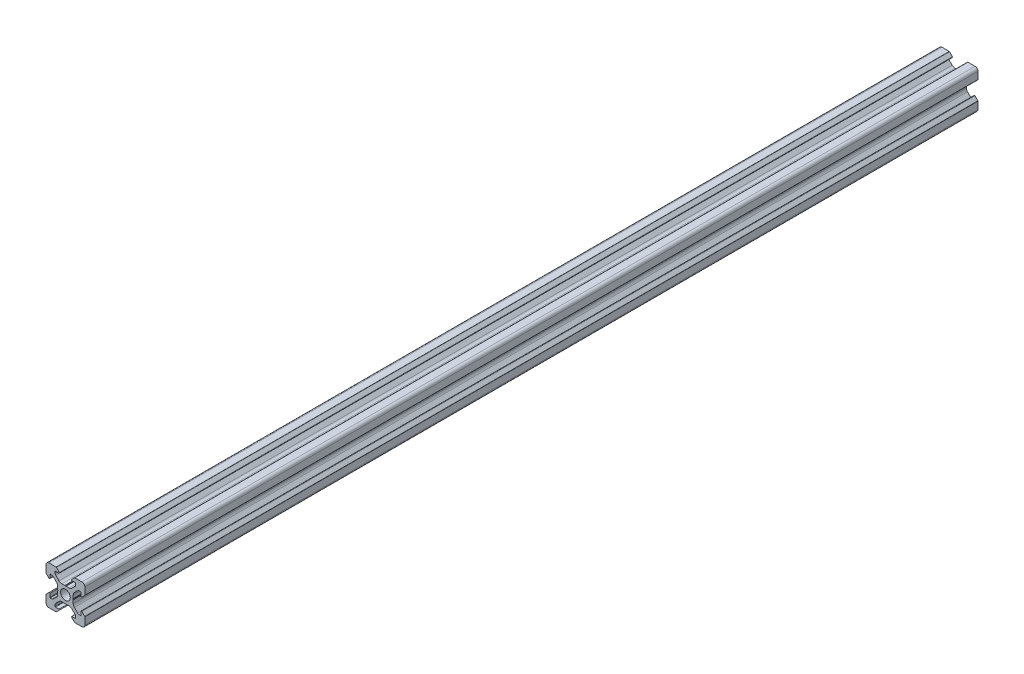
SolidWorks part; units mm, degrees
ref_plane "Спереди" through (0, 0, 0) normal (0, 0, 1) x (1, 0, 0)
ref_plane "Сверху" through (0, 0, 0) normal (0, 1, 0) x (1, 0, 0)
ref_plane "Справа" through (0, 0, 0) normal (1, 0, 0) x (0, 0, -1)
sketch "Model" plane through (0, 0, 0) normal (0, 0, 1) x (1, 0, 0)
  line L0 (18.9421, 33.3622) -> (18.9421, 34.9233)
  line L1 (18.3564, 36.3375) -> (16.6623, 38.0316)
  line L2 (15.9551, 38.3245) -> (15.1421, 38.3245)
  line L3 (14.9421, 38.1245) -> (14.9421, 36.3545)
  line L4 (13.0154, 37.6777) -> (14.5154, 36.1777)
  line L5 (12.9421, 37.8545) -> (12.9421, 41.5245)
  line L6 (18.2889, 42.9513) -> (19.7889, 41.4513)
  line L7 (22.7606, 36.9697) -> (22.9421, 36.8245)
  line L8 (23.1237, 36.9697) -> (22.9421, 36.8245)
  line L9 (23.2798, 37.0245) -> (24.8409, 37.0245)
  line L10 (26.2551, 37.6103) -> (27.9493, 39.3044)
  line L11 (28.2421, 40.0115) -> (28.2421, 40.8245)
  line L12 (28.0421, 41.0245) -> (26.2721, 41.0245)
  line L13 (27.5954, 42.9513) -> (26.0954, 41.4513)
  line L14 (27.7721, 43.0245) -> (31.4421, 43.0245)
  line L15 (32.9421, 37.8545) -> (32.9421, 41.5245)
  line L16 (32.8689, 37.6777) -> (31.3689, 36.1777)
  line L17 (30.9421, 38.1245) -> (30.9421, 36.3545)
  line L18 (29.9292, 38.3245) -> (30.7421, 38.3245)
  line L19 (27.5279, 36.3375) -> (29.222, 38.0316)
  line L20 (26.9421, 33.3622) -> (26.9421, 34.9233)
  line L21 (26.8874, 33.206) -> (26.7421, 33.0245)
  line L22 (26.8874, 32.843) -> (26.7421, 33.0245)
  line L23 (26.9421, 32.6868) -> (26.9421, 31.1257)
  line L24 (27.5279, 29.7115) -> (29.222, 28.0174)
  line L25 (29.9292, 27.7245) -> (30.7421, 27.7245)
  line L26 (30.9421, 27.9245) -> (30.9421, 29.6945)
  line L27 (32.8689, 28.3713) -> (31.3689, 29.8713)
  line L28 (32.9421, 28.1945) -> (32.9421, 24.5245)
  line L29 (27.7721, 23.0245) -> (31.4421, 23.0245)
  line L30 (27.5954, 23.0977) -> (26.0954, 24.5977)
  line L31 (28.0421, 25.0245) -> (26.2721, 25.0245)
  line L32 (28.2421, 26.0375) -> (28.2421, 25.2245)
  line L33 (26.2551, 28.4387) -> (27.9493, 26.7446)
  line L34 (23.2798, 29.0245) -> (24.8409, 29.0245)
  line L35 (23.1237, 29.0793) -> (22.9421, 29.2245)
  line L36 (22.7606, 29.0793) -> (22.9421, 29.2245)
  line L37 (19.6292, 28.4387) -> (17.935, 26.7446)
  line L38 (17.6421, 26.0375) -> (17.6421, 25.2245)
  line L39 (17.8421, 25.0245) -> (19.6121, 25.0245)
  line L40 (18.2889, 23.0977) -> (19.7889, 24.5977)
  line L41 (18.1121, 23.0245) -> (14.4421, 23.0245)
  line L42 (12.9421, 28.1945) -> (12.9421, 24.5245)
  line L43 (13.0154, 28.3713) -> (14.5154, 29.8713)
  line L44 (14.9421, 27.9245) -> (14.9421, 29.6945)
  line L45 (15.9551, 27.7245) -> (15.1421, 27.7245)
  line L46 (18.3564, 29.7115) -> (16.6623, 28.0174)
  line L47 (18.9421, 32.6868) -> (18.9421, 31.1257)
  line L48 (18.9969, 32.843) -> (19.1421, 33.0245)
  line L49 (18.9969, 33.206) -> (19.1421, 33.0245)
  line L50 (22.6045, 29.0245) -> (21.0434, 29.0245)
  line L51 (22.6045, 37.0245) -> (21.0434, 37.0245)
  line L52 (19.6292, 37.6103) -> (17.935, 39.3044)
  line L53 (17.6421, 40.0115) -> (17.6421, 40.8245)
  line L54 (17.8421, 41.0245) -> (19.6121, 41.0245)
  line L55 (18.1121, 43.0245) -> (14.4421, 43.0245)
  arc A0 (18.9421, 33.3622) -> (18.9969, 33.206) centre (19.1921, 33.3622) ccw
  arc A1 (18.9421, 34.9233) -> (18.3564, 36.3375) centre (16.9421, 34.9233) ccw
  arc A2 (16.6623, 38.0316) -> (15.9551, 38.3245) centre (15.9551, 37.3245) ccw
  arc A3 (15.1421, 38.3245) -> (14.9421, 38.1245) centre (15.1421, 38.1245) ccw
  arc A4 (14.5154, 36.1777) -> (14.9421, 36.3545) centre (14.6921, 36.3545) ccw
  arc A5 (12.9421, 37.8545) -> (13.0154, 37.6777) centre (13.1921, 37.8545) ccw
  arc A6 (14.4421, 43.0245) -> (12.9421, 41.5245) centre (14.4421, 41.5245) ccw
  arc A7 (18.2889, 42.9513) -> (18.1121, 43.0245) centre (18.1121, 42.7745) ccw
  arc A8 (19.6121, 41.0245) -> (19.7889, 41.4513) centre (19.6121, 41.2745) ccw
  arc A9 (17.8421, 41.0245) -> (17.6421, 40.8245) centre (17.8421, 40.8245) ccw
  arc A10 (17.6421, 40.0115) -> (17.935, 39.3044) centre (18.6421, 40.0115) ccw
  arc A11 (19.6292, 37.6103) -> (21.0434, 37.0245) centre (21.0434, 39.0245) ccw
  arc A12 (22.7606, 36.9697) -> (22.6045, 37.0245) centre (22.6045, 36.7745) ccw
  arc A13 (23.2798, 37.0245) -> (23.1237, 36.9697) centre (23.2798, 36.7745) ccw
  arc A14 (24.8409, 37.0245) -> (26.2551, 37.6103) centre (24.8409, 39.0245) ccw
  arc A15 (27.9493, 39.3044) -> (28.2421, 40.0115) centre (27.2421, 40.0115) ccw
  arc A16 (28.2421, 40.8245) -> (28.0421, 41.0245) centre (28.0421, 40.8245) ccw
  arc A17 (26.0954, 41.4513) -> (26.2721, 41.0245) centre (26.2721, 41.2745) ccw
  arc A18 (27.7721, 43.0245) -> (27.5954, 42.9513) centre (27.7721, 42.7745) ccw
  arc A19 (32.9421, 41.5245) -> (31.4421, 43.0245) centre (31.4421, 41.5245) ccw
  arc A20 (32.8689, 37.6777) -> (32.9421, 37.8545) centre (32.6921, 37.8545) ccw
  arc A21 (30.9421, 36.3545) -> (31.3689, 36.1777) centre (31.1921, 36.3545) ccw
  arc A22 (30.9421, 38.1245) -> (30.7421, 38.3245) centre (30.7421, 38.1245) ccw
  arc A23 (29.9292, 38.3245) -> (29.222, 38.0316) centre (29.9292, 37.3245) ccw
  arc A24 (27.5279, 36.3375) -> (26.9421, 34.9233) centre (28.9421, 34.9233) ccw
  arc A25 (26.8874, 33.206) -> (26.9421, 33.3622) centre (26.6921, 33.3622) ccw
  arc A26 (26.9421, 32.6868) -> (26.8874, 32.843) centre (26.6921, 32.6868) ccw
  arc A27 (26.9421, 31.1257) -> (27.5279, 29.7115) centre (28.9421, 31.1257) ccw
  arc A28 (29.222, 28.0174) -> (29.9292, 27.7245) centre (29.9292, 28.7245) ccw
  arc A29 (30.7421, 27.7245) -> (30.9421, 27.9245) centre (30.7421, 27.9245) ccw
  arc A30 (31.3689, 29.8713) -> (30.9421, 29.6945) centre (31.1921, 29.6945) ccw
  arc A31 (32.9421, 28.1945) -> (32.8689, 28.3713) centre (32.6921, 28.1945) ccw
  arc A32 (31.4421, 23.0245) -> (32.9421, 24.5245) centre (31.4421, 24.5245) ccw
  arc A33 (27.5954, 23.0977) -> (27.7721, 23.0245) centre (27.7721, 23.2745) ccw
  arc A34 (26.2721, 25.0245) -> (26.0954, 24.5977) centre (26.2721, 24.7745) ccw
  arc A35 (28.0421, 25.0245) -> (28.2421, 25.2245) centre (28.0421, 25.2245) ccw
  arc A36 (28.2421, 26.0375) -> (27.9493, 26.7446) centre (27.2421, 26.0375) ccw
  arc A37 (26.2551, 28.4387) -> (24.8409, 29.0245) centre (24.8409, 27.0245) ccw
  arc A38 (23.1237, 29.0793) -> (23.2798, 29.0245) centre (23.2798, 29.2745) ccw
  arc A39 (22.6045, 29.0245) -> (22.7606, 29.0793) centre (22.6045, 29.2745) ccw
  arc A40 (21.0434, 29.0245) -> (19.6292, 28.4387) centre (21.0434, 27.0245) ccw
  arc A41 (17.935, 26.7446) -> (17.6421, 26.0375) centre (18.6421, 26.0375) ccw
  arc A42 (17.6421, 25.2245) -> (17.8421, 25.0245) centre (17.8421, 25.2245) ccw
  arc A43 (19.7889, 24.5977) -> (19.6121, 25.0245) centre (19.6121, 24.7745) ccw
  arc A44 (18.1121, 23.0245) -> (18.2889, 23.0977) centre (18.1121, 23.2745) ccw
  arc A45 (12.9421, 24.5245) -> (14.4421, 23.0245) centre (14.4421, 24.5245) ccw
  arc A46 (13.0154, 28.3713) -> (12.9421, 28.1945) centre (13.1921, 28.1945) ccw
  arc A47 (14.9421, 29.6945) -> (14.5154, 29.8713) centre (14.6921, 29.6945) ccw
  arc A48 (14.9421, 27.9245) -> (15.1421, 27.7245) centre (15.1421, 27.9245) ccw
  arc A49 (15.9551, 27.7245) -> (16.6623, 28.0174) centre (15.9551, 28.7245) ccw
  arc A50 (18.3564, 29.7115) -> (18.9421, 31.1257) centre (16.9421, 31.1257) ccw
  arc A51 (18.9969, 32.843) -> (18.9421, 32.6868) centre (19.1921, 32.6868) ccw
  circle A52 centre (22.9421, 33.0245) radius 2.5
extrude "Бобышка-Вытянуть1" add sketch "Model" along normal blind 460
